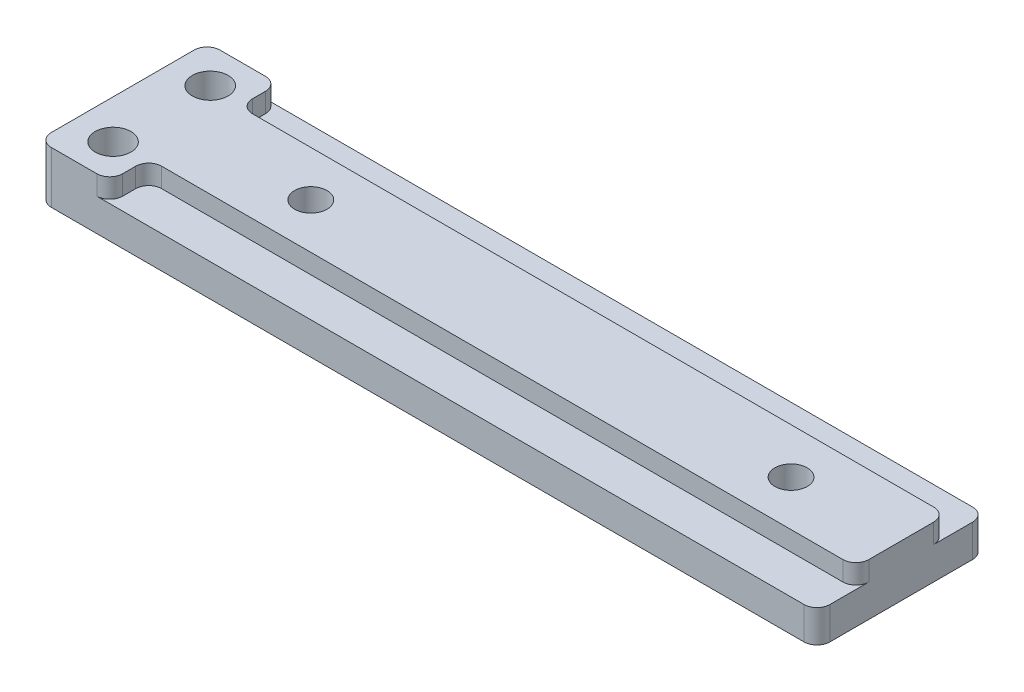
SolidWorks part; units mm, degrees
ref_plane "Front Plane" through (0, 0, 0) normal (0, 0, 1) x (1, 0, 0)
ref_plane "Top Plane" through (0, 0, 0) normal (0, 1, 0) x (1, 0, 0)
ref_plane "Right Plane" through (0, 0, 0) normal (1, 0, 0) x (0, 0, -1)
sketch "Sketch1" plane through (0, 0, 0) normal (0, 1, 0) x (1, 0, 0)
  line L0 (0, 0) -> (0, 33.02)
  line L1 (0, 33.02) -> (152.4, 33.02)
  line L2 (152.4, 33.02) -> (152.4, 0)
  line L3 (152.4, 0) -> (0, 0)
  line L4 (0, 16.51) -> (7.62, 16.51) construction
  line L5 (7.62, 33.02) -> (7.62, 26.02) construction
  line L6 (7.62, 26.02) -> (15.24, 26.02) construction
  line L7 (15.24, 33.02) -> (15.24, 0) construction
  line L8 (15.24, 16.51) -> (152.4, 16.51) construction
  line L9 (83.82, 16.51) -> (83.82, 33.02) construction
  circle A1 centre (7.62, 26.02) radius 3.5
  circle A2 centre (7.62, 7) radius 3.5
  circle A3 centre (130.82, 16.51) radius 3.175
  circle A4 centre (36.82, 16.51) radius 3.175
  dimension "D4" = 7
  dimension "D5" = 7
  dimension "D9" = 6.35
  dimension "D10" = 6.35
  dimension "D1" = 33.02
  dimension "D2" = 152.4
  dimension "D3" = 7.62
  dimension "D6" = 7.62
  dimension "D7" = 47
  dimension "D8" = 47
extrude "Boss-Extrude1" add sketch "Sketch1" along normal blind 10.16
sketch "Sketch3" plane through (152.4, 0, 0) normal (1, 0, 0) x (0, 0, -1)
  line L0 (16.51, 10.16) -> (16.51, 0) construction
  line L1 (0, 10.16) -> (33.02, 10.16) construction
  line L2 (0, 0) -> (33.02, 0) construction
  line L3 (0, 10.16) -> (7.62, 10.16)
  line L4 (7.62, 10.16) -> (7.62, 6.35)
  line L5 (7.62, 6.35) -> (0, 6.35)
  line L6 (0, 10.16) -> (0, 0) construction
  line L7 (0, 6.35) -> (0, 10.16)
  line L8 (25.4, 10.16) -> (25.4, 6.35)
  line L9 (25.4, 6.35) -> (33.02, 6.35)
  line L10 (33.02, 6.35) -> (33.02, 10.16)
  line L11 (33.02, 10.16) -> (25.4, 10.16)
  dimension "D1" = 3.81
  dimension "D2" = 7.62
extrude "Cut-Extrude1" cut sketch "Sketch3" against normal blind 138.43
fillet "Fillet1" radius 2.54 10 edges at (152.4, 3.175, -33.02) (152.4, 8.255, -25.4) (152.4, 3.175, 0) (152.4, 8.255, -7.62) (13.97, 8.255, 0) (13.97, 8.255, -7.62) (13.97, 8.255, -25.4) (13.97, 8.255, -33.02) (0, 5.08, -33.02) (0, 5.08, 0)
